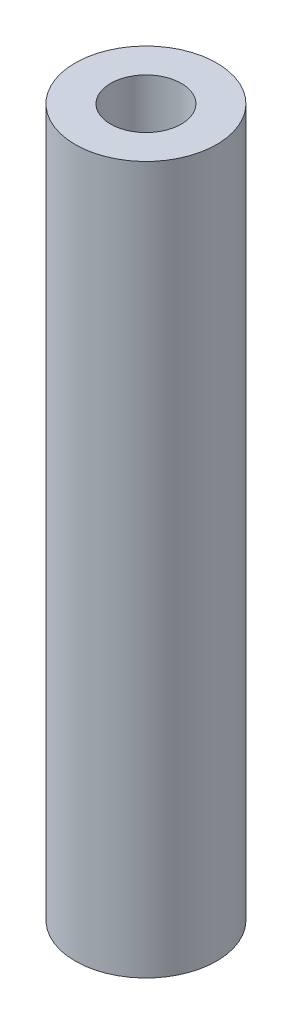
SolidWorks part; units mm, degrees
ref_plane "Front Plane" through (0, 0, 0) normal (0, 0, 1) x (1, 0, 0)
ref_plane "Top Plane" through (0, 0, 0) normal (0, 1, 0) x (1, 0, 0)
ref_plane "Right Plane" through (0, 0, 0) normal (1, 0, 0) x (0, 0, -1)
sketch "Sketch2" plane through (0, 0, 0) normal (0, 1, 0) x (1, 0, 0)
  circle A0 centre (0, 0) radius 5
  dimension "D1" = 10
extrude "Boss-Extrude1" add sketch "Sketch2" along normal blind 50 contours A0
sketch "Sketch3" plane through (0, 50, 0) normal (0, 1, 0) x (1, 0, 0)
  circle A0 centre (0, 0) radius 2.5
  dimension "D1" = 5
extrude "Cut-Extrude1" cut sketch "Sketch3" against normal blind 30 contours A0
